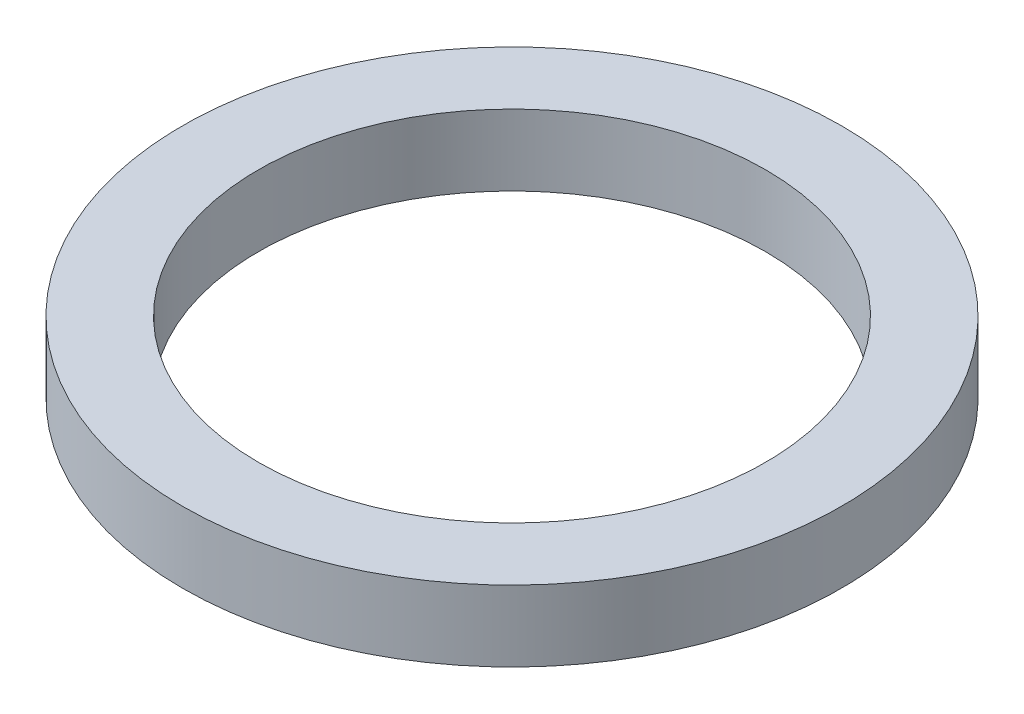
SolidWorks part; units mm, degrees
ref_plane "Front Plane" through (0, 0, 0) normal (0, 0, 1) x (1, 0, 0)
ref_plane "Top Plane" through (0, 0, 0) normal (0, 1, 0) x (1, 0, 0)
ref_plane "Right Plane" through (0, 0, 0) normal (1, 0, 0) x (0, 0, -1)
sketch "Sketch1" plane through (0, 0, 0) normal (0, 1, 0) x (1, 0, 0)
  circle A0 centre (0, 0) radius 25
  circle A1 centre (0, 0) radius 32.5
  dimension "D1" = 50
  dimension "D2" = 65
extrude "Boss-Extrude1" add sketch "Sketch1" along normal mid plane 7
equation "\"Nr\" = 123"
equation "\"module\" = 0.5"
equation "\"pressure_angle\" = 20.0"
equation "\"h_a\" = 0.5"
equation "\"h_f\" = 0.625"
equation "\"clr_tip_root\" = 0.125"
equation "\"dp_r\" = 61.5"
equation "\"db_r\" = 57.79109617833337"
equation "\"fw_r\" = 8.0"
equation "\"alpha_r\" = 0.8539582918412414"
equation "\"beta_r\" = 3.171331217828824"
equation "\"bearing_ID\" = 50"
equation "\"bearing_OD\" = 65"
equation "\"bearing_height\" = 7"
equation "\"clearance_planet\" = 1.5"
equation "\"case_dist\" = 6.0"
equation "\"Motor_case_OD_max\" = 96.5"
equation "\"case_mounting_PCD\" = 89.0"
equation "\"bearing mount thickness\" = 8"
equation "\"case_mounting_hole_dia\" = 3"
equation "\"output_mounting_PCD\" = 73"
equation "\"output_mounting_hole_dia\" = 4"
equation "\"clearance_case_mount_holes_shell_thickness\" = 1"
equation "\"motor_case_OD_base\" = 87.0"
equation "\"sec_carrier_thickness\" = 5"
equation "\"sun_coupler_hub_thickness\" = 4"
equation "\"clearance_sun_coupler_sec_carrier\" = 1.5"
equation "\"clearance_motor_and_case\" = 5"
equation "\"motor_OD\" = 72"
equation "\"Motor_case_thickness\" = 2.5"
equation "\"Motor_case_ID\" = 82"
equation "\"case_mounting_hole_shift\" = 1.0"
equation "\"output_mounting_nut_wrench_size\" = 7"
equation "\"output_mounting_nut_thickness\" = 3.2"
equation "\"case_mounting_hole_allen_socket_dia\" = 5.5"
equation "\"output_mounting_nut_depth\" = 3"
equation "\"case_mounting_bolt_depth\" = 4.5"
equation "\"Ns\" = 33"
equation "\"Np\" = 45"
equation "\"ring_radial_thickness\" = 5"
equation "\"ring_OD\" = 71.5"
equation "\"ring_to_chamfer_clearance\" = 2"
equation "\"Motor_case_OD_base_to_chamfer\" = 5"
equation "\"pattern_offset_from_motor_case_OD_base\" = 3"
equation "\"pattern_bulge_dia\" = 3"
equation "\"pattern_num_bulge\" = 18"
equation "\"pattern_depth\" = 2"
equation "\"motor_height\" = 27"
equation "\"case_mounting_wrench_size\" = 5.5"
equation "\"case_mounting_nut_clearance\" = 2"
equation "\"base_plate_thickness\" = 4"
equation "\"case_mounting_nut_thickness\" = 2.4"
equation "\"case_mounting_surface_height\" = 4"
equation "\"motor_mount_hole_PCD\" = 32"
equation "\"motor_mount_hole_dia\" = 4"
equation "\"motor_mount_hole_num\" = 4"
equation "\"central_hole_offset_from_motor_mount_PCD\" = 5"
equation "\"wire_slot_dist_from_center\" = 30"
equation "\"wire_slot_length\" = 10"
equation "\"wire_slot_radius\" = 2.5"
equation "\"driver_upper_holes_dist_from_center\" = 23"
equation "\"driver_lower_holes_dist_from_center\" = 15"
equation "\"driver_side_holes_dist_from_center\" = 20"
equation "\"driver_mount_holes_dia\" = 2.5"
equation "\"driver_mount_inserts_OD\" = 3.5"
equation "\"driver_mount_thickness\" = 1.5"
equation "\"driver_mount_height\" = 4"
equation "\"air_flow_hole_offset\" = 3"
equation "\"num_planet\" = 3"
equation "\"planet_pin_bolt_dia\" = 5"
equation "\"planet_pin_socket_head_dia\" = 8.5"
equation "\"carrier_PCD\" = 39.0"
equation "\"planet_shaft_dia\" = 8"
equation "\"fw_p\" = 8.0"
equation "\"planet_shaft_step_offset\" = 1"
equation "\"carrier_trapezoidal_support_sun_offset\" = 5"
equation "\"carrier_trapezoidal_support_hole_PCD_offset_bearing_ID\" = 4"
equation "\"carrier_trapezoidal_support_hole_dia\" = 3"
equation "\"carrier_trapezoidal_support_hole_socket_head_dia\" = 5.5"
equation "\"carrier_bearing_step_width\" = 1.5"
equation "\"standard_clearance_1_5mm\" = 1.5"
equation "\"standard_fillet_1_5mm\" = 1.5"
equation "\"sun_shaft_bearing_OD\" = 16"
equation "\"sun_shaft_bearing_width\" = 5"
equation "\"standard_bearing_insertion_chamfer\" = 0.5"
equation "\"D1@Sketch1\"=\"bearing_ID\""
equation "\"D2@Sketch1\"=\"bearing_OD\""
equation "\"D1@Boss-Extrude1\"=\"bearing_height\""
equation "\"D7@Sketch2\"=\"carrier_trapezoidal_support_hole_dia\""
equation "\"D5@Sketch2\"= 360 / ( 4 * \"Ns\" ) - \"alpha_s\""
equation "\"D3@Sketch2\"=\"dp_s\"- 2*\"h_b\""
equation "\"D9@Sketch2\"=\"carrier_trapezoidal_support_sun_offset\""
equation "\"carrier_trapezoidal_support_hole_wrench_size\" = 5.5"
equation "\"planet_pin_bolt_wrench_size\" = 8"
equation "\"pressure angle\" = 20.0"
equation "\"motor_output_hole_PCD\" = 22"
equation "\"motor_output_hole_dia\" = 3"
equation "\"motor_output_hole_num\" = 4"
equation "\"h_b\" = 0.625"
equation "\"dp_s\" = 16.5"
equation "\"db_s\" = 15.50492824296749"
equation "\"fw_s_calc\" = 5.95406185839039"
equation "\"alpha_s\" = 0.8539582918412449"
equation "\"beta_s\" = 3.7466288708629643"
equation "\"dp_p\" = 22.5"
equation "\"db_p\" = 21.14308396768294"
equation "\"alpha_p\" = 0.8539582918412307"
equation "\"beta_p\" = 2.2920834163175385"
equation "\"planet_bearing_OD\" = 12"
equation "\"planet_bearing_width\" = 3.5"
equation "\"planet_bore\" = 10"
equation "\"sun_shaft_bearing_ID\" = 8"
equation "\"sun_hub_dia\" = 31.0"
equation "\"sun_central_bolt_dia\" = 5"
equation "\"sun_central_bolt_socket_head_dia\" = 8.5"
equation "\"fw_s_used\" = 16.0"
equation "\"motor_output_hole_CSK_OD\" = 6"
equation "\"motor_output_hole_CSK_head_height\" = 1.5"
equation "\"bearing_retainer_thickness\" = 2"
equation "\"Ns1\" = 33"
equation "\"Np1\" = 45"
equation "\"Nr1\" = 123"
equation "\"module1\" = 0.5"
equation "\"bearing1_ID\" = 50"
equation "\"bearing1_OD\" = 65"
equation "\"bearing1_height1\" = 7"
equation "\"bearing mount thickness1\" = 8"
equation "\"output_mounting_PCD1\" = 73"
